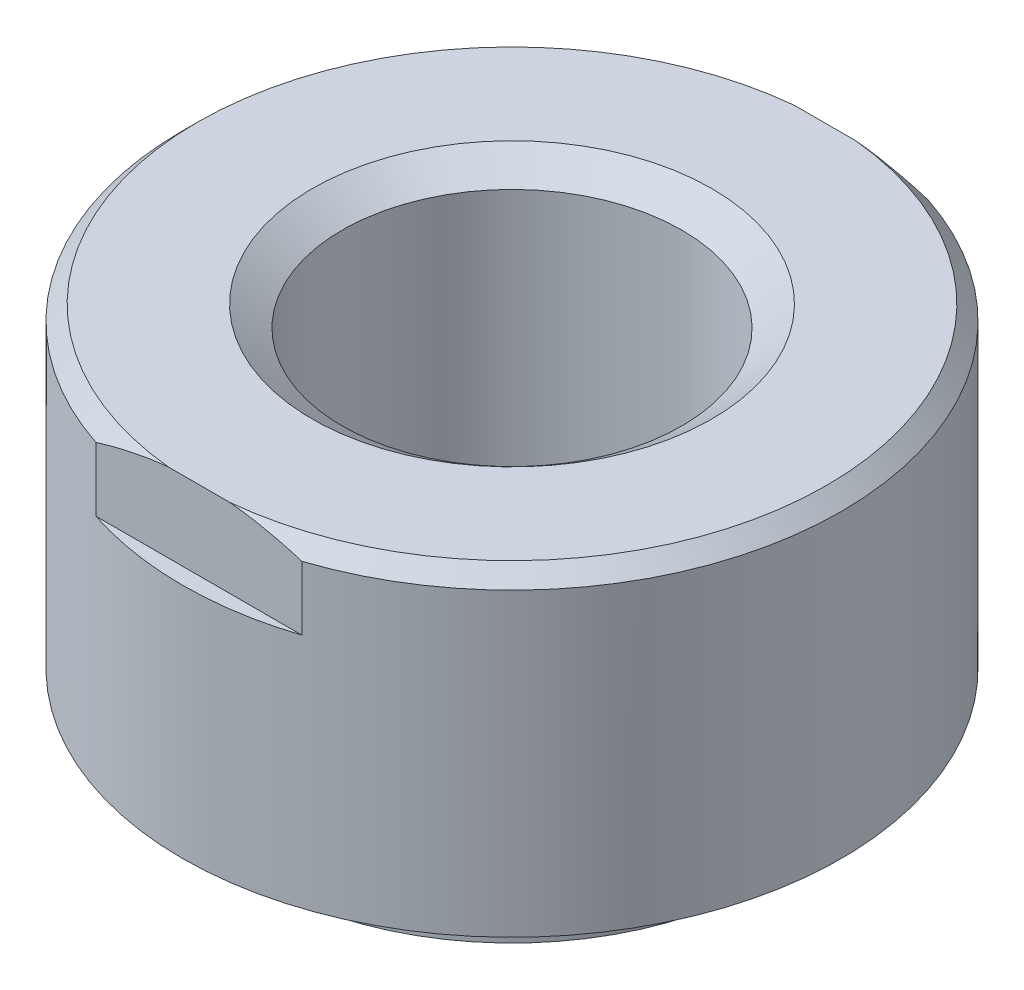
SolidWorks part; units mm, degrees
revolve "Body" add sketch "BodySke"
sketch "BodySke" plane through (0, 0, 0) normal (0, 0, 1) x (1, 0, 0)
  line L0 (5.8956, 0) -> (6.335, 0)
  line L1 (8.25, 0) -> (8.25, 7.9)
  line L2 (8.25, 7.9) -> (4.25, 7.9)
  line L3 (4.25, 7.9) -> (4.25, -1.48)
  line L4 (4.25, -1.48) -> (6.335, -1.48)
  line L5 (6.335, -1.48) -> (6.335, -1.353)
  line L6 (6.335, -1.353) -> (5.8956, -0.592)
  line L7 (1.016, 1.5) -> (3.6522, 1.5) construction
  line L8 (6.335, -0.592) -> (7.2925, -0.592)
  line L9 (0, 0) -> (0, 15.24) construction
  line L10 (5.8956, -0.592) -> (5.8956, 0)
  line L11 (7.2925, -0.592) -> (7.2925, 0)
  line L12 (6.335, -0.592) -> (6.335, 0)
  line L13 (7.2925, 0) -> (8.25, 0)
  dimension "D1" = 60
  dimension "E_dia" = 16.5
  dimension "C_dia" = 12.67
  dimension "A_ht" = 1.48
  dimension "T_ht" = 7.9
  dimension "Thread_min" = 8.5
  dimension "C_len" = 0.127
  dimension "Clinching_ht" = 0.592
  dimension "Advance" = 1.5
  dimension "Clinching_dia" = 14.585
cosmetic thread "ThreadCosmetic" [suppressed]
revolve "EndChamfer" cut sketch "EndChamferSke" angle 360 about L0
sketch "EndChamferSke" plane through (0, 0, 0) normal (0, 0, 1) x (1, 0, 0)
  line L0 (0, -2.54) -> (0, 7.62) construction
  line L1 (0, 0) -> (0, 15.24) construction
  line L2 (5, -1.734) -> (5, -1.4775)
  line L3 (5, -1.4775) -> (4.25, -0.9525)
  line L4 (4.25, -0.9525) -> (4.25, -1.734)
  line L5 (4.25, -1.734) -> (5, -1.734)
  line L6 (5, 7.9) -> (4.25, 7.375)
  line L8 (4.25, 7.375) -> (4.25, 7.9)
  line L9 (5, 7.9) -> (4.25, 7.9)
  line L10 (4.25, 7.9) -> (-4.25, 7.9) construction
  line L11 (-6.335, -1.48) -> (6.335, -1.48) construction
  dimension "D1" = 0.254
  dimension "Thread_nominal" = 10
  dimension "D2" = 34.99
  dimension "Thread_min" = 8.5
  dimension "Inset" = 0.0025
ref_plane "Plane1" through (0, 0, 0) normal (0, 0, 1) x (1, 0, 0)
ref_plane "Plane2" through (0, 0, 0) normal (0, 1, 0) x (1, 0, 0)
ref_plane "Plane3" through (0, 0, 0) normal (1, 0, 0) x (0, 0, -1)
chamfer "Chamfer" distance 0.375 1 edges at (0, 7.9, -8.25)
sketch "FlatsSke" plane through (0, 7.9, 0) normal (0, 1, 0) x (-1, 0, 0)
  line L0 (-8.25, 7.8375) -> (8.25, 7.8375)
  line L1 (8.25, 7.8375) -> (8.25, 8.6625)
  line L2 (8.25, 8.6625) -> (-8.25, 8.6625)
  line L3 (-8.25, 8.6625) -> (-8.25, 7.8375)
  line L4 (-8.25, -7.8375) -> (8.25, -7.8375)
  line L5 (8.25, -7.8375) -> (8.25, -8.6625)
  line L6 (8.25, -8.6625) -> (-8.25, -8.6625)
  line L7 (-8.25, -8.6625) -> (-8.25, -7.8375)
  line L8 (0, 9.144) -> (0, -9.144) construction
  line L9 (-9.144, 0) -> (9.144, 0) construction
  dimension "D1" = 16.5
  dimension "D2" = 15.675
  dimension "D3" = 17.325
extrude "Flats" cut sketch "FlatsSke" against normal blind 1.975
ref_plane "Plane4" through (0, -0.5486, 0) normal (0, 1, 0) x (-1, 0, 0)
sketch "ThdSchSke" plane through (0, 0, 0) normal (0, 0, 1) x (1, 0, 0)
  line L0 (0, -5.08) -> (0, 7.62) construction
  line L1 (0, 0) -> (0, 15.24) construction
  line L2 (0, -1.4775) -> (5, -1.4775) construction
  line L4 (5, -1.4775) -> (4.25, -0.9523)
  line L6 (5, -1.4775) -> (4.25, -2.0026)
  line L7 (4.25, -0.9523) -> (4.25, -2.0026)
  line L8 (5, -1.4775) -> (-5, -1.4775) construction
  dimension "Thread_nominal" = 10
revolve "ThreadSchematic" [suppressed] cut sketch "ThdSchSke" angle 360 about L0
pattern_linear "ThdSchPat" [suppressed]
sketch "CliCutSke" plane through (0, -0.592, 0) normal (0, -1, 0) x (1, 0, 0)
  line L0 (0, 0) -> (0, 8.382) construction
  line L1 (0, 0) -> (0.9519, 7.2301) construction
  circle A0 centre (0.9519, 7.2301) radius 0.825
  circle A1 centre (0, 0) radius 7.2925 construction
extrude "ClinchingCut" cut sketch "CliCutSke" against normal blind 0.592
pattern_circular "ClinchingCutPat" count 24 every 15 about axis through (0, 0, 0) along (0, 1, 0) of "ClinchingCut"
equation "' \"A_ht@BodySke\" = 1.48"
equation "' \"C_dia@BodySke\" = 12.67"
equation "' \"E_dia@BodySke\" = 16.5"
equation "' \"T_ht@BodySke\" = 7.9"
equation "' \"Advance@BodySke\" = 1.5"
equation "' \"Thread_min@BodySke\" = 8.5"
equation "' \"Thread_nominal@ThreadCosmetic\" = 10"
equation "\"Count@ClinchingCutPat\" = 24"
equation "\"Angle@ClinchingCutPat\" = 360 / \"Count@ClinchingCutPat\""
equation "\"Half_angle@CliCutSke\" = 180 / \"Count@ClinchingCutPat\""
equation "\"Cut_dia@CliCutSke\" = \"E_dia@BodySke\" * 0.1"
equation "\"Clinching_dia@BodySke\" = ( \"E_dia@BodySke\" + \"C_dia@BodySke\" ) /2"
equation "\"Clinching_ht@BodySke\" = \"A_ht@BodySke\" * 0.4"
equation "\"Clinching_ht@ClinchingCut\" =  \"A_ht@BodySke\" * 0.4"
equation "\"D1@FlatsSke\" = \"E_dia@BodySke\""
equation "\"D2@FlatsSke\" = \"E_dia@BodySke\" * 0.95"
equation "\"D3@FlatsSke\" = \"E_dia@BodySke\" * 1.05"
equation "\"Depth@Flats\" = \"T_ht@BodySke\" * 0.25"
equation "\"Width@Chamfer\" = ( \"Thread_nominal@ThreadCosmetic\" - \"Thread_min@BodySke\" ) / 4"
equation "\"Thread_nominal@EndChamferSke\" = \"Thread_nominal@ThreadCosmetic\""
equation "\"Thread_min@EndChamferSke\" = \"Thread_min@BodySke\""
equation "\"D2@EndChamferSke\" = \"Vee_angle@ThdSchSke\" / 2 - 0.01"
equation "\"Thread_nominal@ThdSchSke\" = \"Thread_nominal@ThreadCosmetic\""
equation "\"Thread_min@ThdSchSke\" = \"Thread_min@BodySke\""
equation "\"Num_threads@ThdSchPat\" = int(  ( \"A_ht@BodySke\" + \"T_ht@BodySke\" - \"Inset@EndChamferSke\" ) / \"Advance@BodySke\" + 0.999 )  + 1"
equation "\"Advance@ThdSchPat\" = (  \"A_ht@BodySke\" + \"T_ht@BodySke\" - \"Inset@EndChamferSke\"  ) /  (\"Num_threads@ThdSchPat\" - 1) 'relax it"
